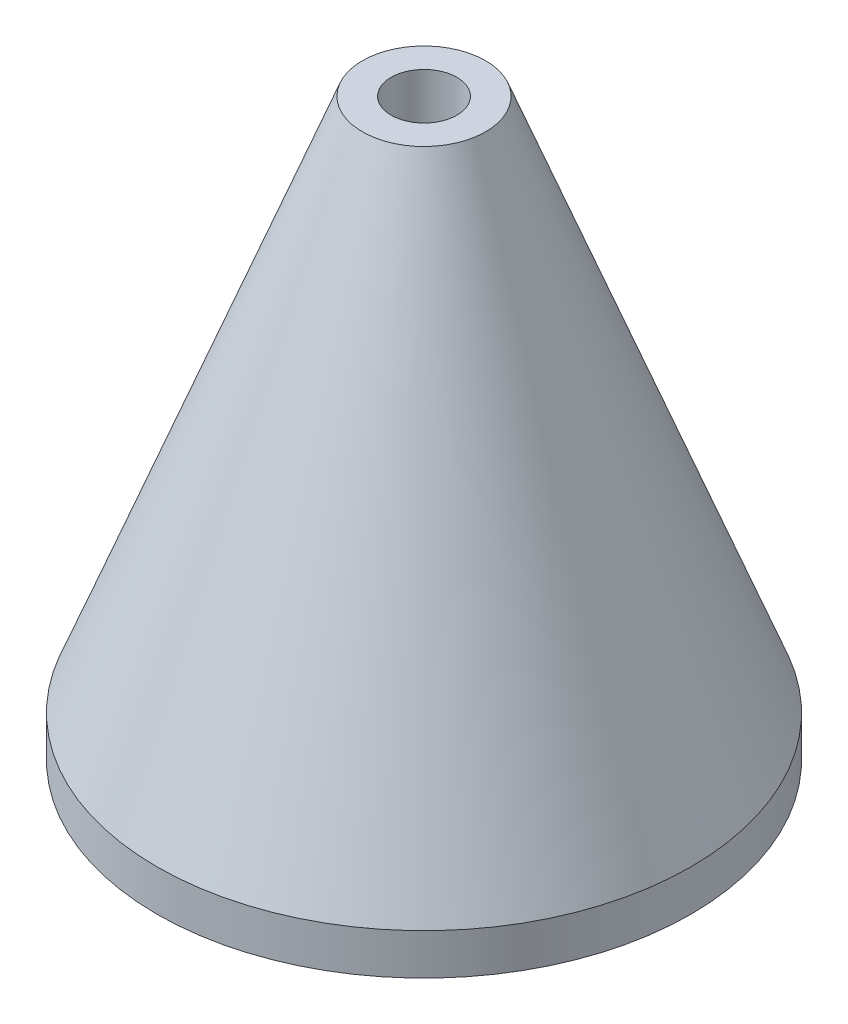
SolidWorks part; units mm, degrees
ref_plane "Přední rovina" through (0, 0, 0) normal (0, 0, 1) x (1, 0, 0)
ref_plane "Horní rovina" through (0, 0, 0) normal (0, 1, 0) x (1, 0, 0)
ref_plane "Pravá rovina" through (0, 0, 0) normal (1, 0, 0) x (0, 0, -1)
sketch "Skica1" plane through (0, 0, 0) normal (0, 0, 1) x (1, 0, 0)
  line L0 (0, 0) -> (0, -50000) construction
  line L1 (0, 0) -> (32.5, 0)
  line L2 (32.5, 5) -> (7.5, 70)
  line L3 (7.5, 70) -> (0, 70)
  line L4 (32.5, 0) -> (32.5, 5)
  line L5 (0, 0) -> (0, 70)
  dimension "D1" = 15
  dimension "D2" = 5
  dimension "D3" = 70
  dimension "D4" = 65
revolve "Rotovat1" add sketch "Skica1" angle 360 about L0
sketch "Skica4" plane through (0, 70, 0) normal (0, 1, 0) x (1, 0, 0)
  circle A0 centre (0, 0) radius 2.1
  dimension "D1" = 4.2
extrude "Odebrat vysunutím2" cut sketch "Skica4" against normal through all both and the other way through all
sketch "Skica6" plane through (0, 70, 0) normal (0, 1, 0) x (1, 0, 0)
  circle A0 centre (0, 0) radius 4
  dimension "D1" = 8
extrude "Odebrat vysunutím3" cut sketch "Skica6" against normal blind 46 and the other way through all
chamfer "Zkosení1" distance 0.5 angle 45 1 edges at (0, 24, 2.1)
